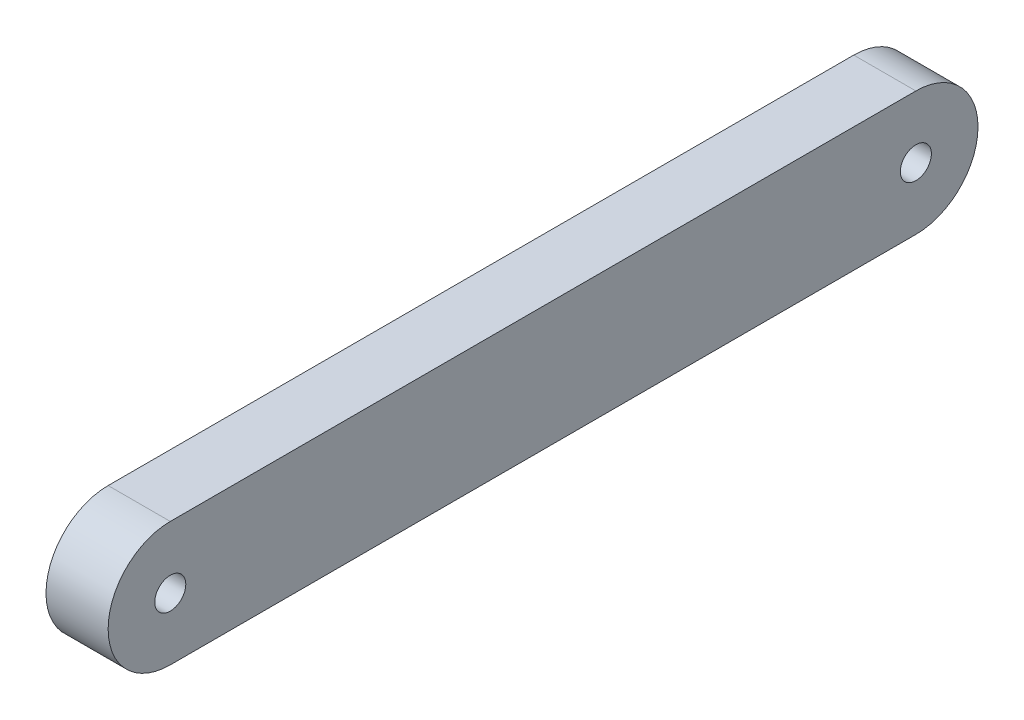
SolidWorks part; units mm, degrees
ref_plane "Front Plane" through (0, 0, 0) normal (1, 0, 0) x (0, 1, 0)
ref_plane "Top Plane" through (0, 0, 0) normal (0, 0, 1) x (0, 1, 0)
ref_plane "Right Plane" through (0, 0, 0) normal (0, 1, 0) x (-1, 0, 0)
sketch "Sketch1" plane through (0, 0, 0) normal (1, 0, 0) x (0, 1, 0)
  line L0 (0, 0) -> (0, 152.4) construction
  line L1 (-12.7, 0) -> (-12.7, 152.4)
  line L2 (12.7, 0) -> (12.7, 152.4)
  arc A0 (-12.7, 0) -> (12.7, 0) centre (0, 0) ccw
  arc A1 (12.7, 152.4) -> (-12.7, 152.4) centre (0, 152.4) ccw
  point P3 (0, 76.2)
  dimension "D1" = 12.7
  dimension "D2" = 152.4
extrude "Boss-Extrude1" add sketch "Sketch1" along normal blind 12.7
sketch "Sketch2" plane through (12.7, 0, 0) normal (1, 0, 0) x (0, 1, 0)
  line L0 (0, 112.8795) -> (0, -19.1174) construction
  line L1 (-12.7, 152.4) -> (12.7, 152.4) construction
  circle A0 centre (0, 0) radius 3.175
  circle A1 centre (0, 152.4) radius 3.175
  dimension "D1" = 6.35
  dimension "D2" = 6.35
extrude "Cut-Extrude1" cut sketch "Sketch2" against normal blind 12.7
